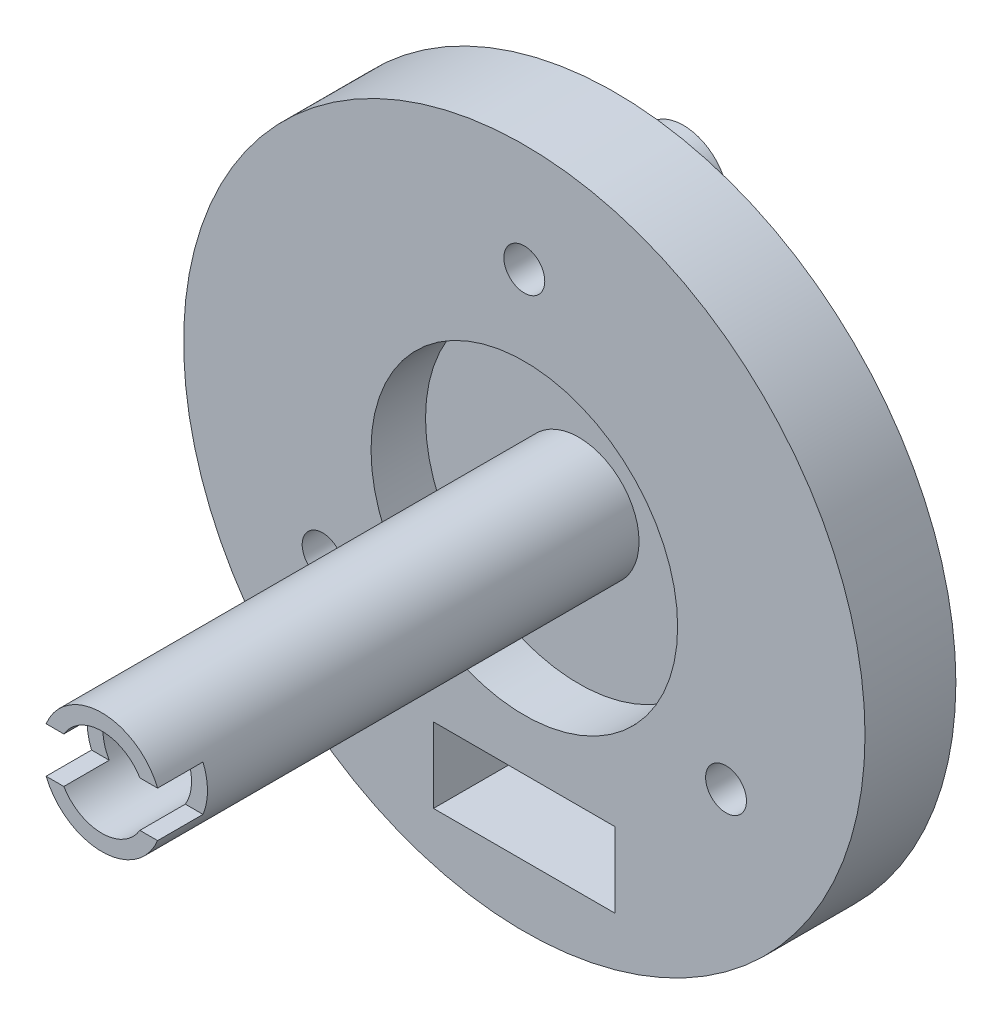
SolidWorks part; units mm, degrees
other "Markup1"
sketch "Sketch7" plane through (190.5, -126, 7) normal (0.1107, -0.2845, 0.9523) x (0.9133, 0.407, 0.0155)
ref_plane "Front Plane" through (0, 0, 0) normal (0, 0, 1) x (1, 0, 0)
ref_plane "Top Plane" through (0, 0, 0) normal (0, 1, 0) x (1, 0, 0)
ref_plane "Right Plane" through (0, 0, 0) normal (1, 0, 0) x (0, 0, -1)
sketch "Sketch1" plane through (0, 0, 0) normal (0, 0, 1) x (1, 0, 0)
  circle A0 centre (166.62, -116.13) radius 2
  circle A1 centre (175.5, -100.75) radius 2
  circle A2 centre (184.38, -116.13) radius 2
  circle A3 centre (166.62, -116.13) radius 0.9
  circle A4 centre (184.38, -116.13) radius 0.9
  circle A5 centre (175.5, -100.75) radius 0.9
  dimension "D1" = 4
extrude "Boss-Extrude1" add sketch "Sketch1" along normal blind 3
sketch "Sketch2" plane through (0, 0, 3) normal (0, 0, 1) x (1, 0, 0)
  circle A0 centre (175.5, -111) radius 15
  circle A1 centre (175.5, -111) radius 1.95
  dimension "D1" = 30
  dimension "D2" = 3.9
extrude "Boss-Extrude2" add sketch "Sketch2" along normal blind 4
sketch "Sketch4" plane through (0, 0, 3) normal (0, 0, -1) x (-1, 0, 0)
  line L1 (-171.5, -120) -> (-179.5, -120)
  line L2 (-171.5, -120) -> (-171.5, -123.3)
  line L3 (-171.5, -123.3) -> (-179.5, -123.3)
  line L4 (-179.5, -120) -> (-179.5, -123.3)
  line L5 (-171.5, -120) -> (-179.5, -123.3) construction
  line L6 (-171.5, -123.3) -> (-179.5, -120) construction
  point P3 (-175.5, -121.65)
  dimension "D1" = 9
  dimension "D2" = 3.3
  dimension "D3" = 8
extrude "Cut-Extrude2" cut sketch "Sketch4" against normal through all contours L1 L4 L3 L2
sketch "Sketch5" plane through (0, 0, 7) normal (0, 0, 1) x (1, 0, 0)
  circle A0 centre (175.5, -111) radius 6.75
  dimension "D1" = 13.5
extrude "Cut-Extrude3" cut sketch "Sketch5" against normal blind 2.4
sketch "Sketch6" plane through (0, 0, 3) normal (0, 0, -1) x (-1, 0, 0)
  line L0 (-175.5, -111) -> (-175.5, -120) construction
  line L1 (-171.5, -120) -> (-179.5, -120) construction
  line L2 (-173.55, -111) -> (-173.55, -120)
  line L3 (-177.45, -111) -> (-177.45, -120)
  arc A0 (-173.55, -111) -> (-177.45, -111) centre (-175.5, -111) ccw
  arc A1 (-177.45, -120) -> (-173.55, -120) centre (-175.5, -120) ccw
  point P5 (-175.5, -115.5)
  dimension "D1" = 1.95
extrude "Cut-Extrude5" cut sketch "Sketch6" against normal blind 1
sketch "Sketch8" plane through (0, 0, 4.6) normal (0, 0, 1) x (1, 0, 0)
  circle A0 centre (175.5, -111) radius 2.65
  circle A2 centre (175.5, -111) radius 1.95
  dimension "D1" = 5.3
  dimension "D2" = 0.7
extrude "Boss-Extrude3" add sketch "Sketch8" along normal blind 21
sketch "Sketch10" plane through (0, 0, 3) normal (0, 0, -1) x (-1, 0, 0)
  circle A0 centre (-175.5, -100.75) radius 0.9
  circle A1 centre (-184.38, -116.13) radius 0.9
  circle A2 centre (-166.62, -116.13) radius 0.9
extrude "Cut-Extrude6" cut sketch "Sketch10" against normal through all
sketch "Sketch11" plane through (0, 0, 25.6) normal (0, 0, 1) x (1, 0, 0)
  line L1 (172, -110) -> (179, -110)
  line L2 (172, -110) -> (172, -112)
  line L3 (172, -112) -> (179, -112)
  line L4 (179, -110) -> (179, -112)
  line L5 (172, -110) -> (179, -112) construction
  line L6 (172, -112) -> (179, -110) construction
  point P0 (175.5, -111)
  dimension "D1" = 2
  dimension "D2" = 7
extrude "Cut-Extrude7" cut sketch "Sketch11" against normal blind 2
